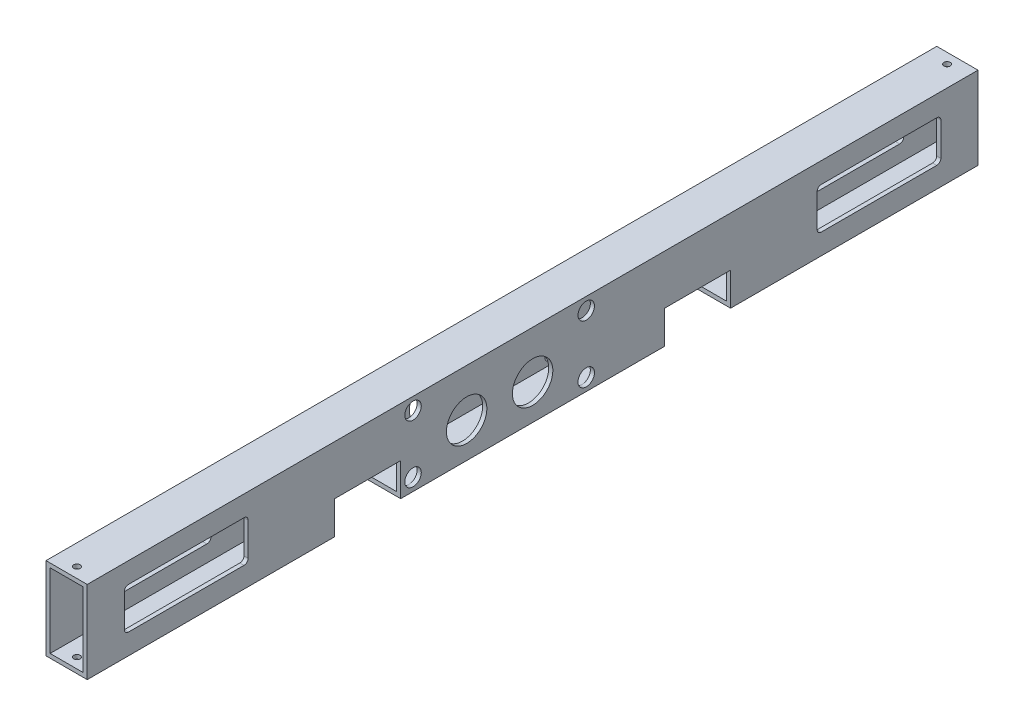
SolidWorks part; units mm, degrees
ref_plane "Front Plane" through (0, 0, 0) normal (0, 0, 1) x (1, 0, 0)
ref_plane "Top Plane" through (0, 0, 0) normal (0, 1, 0) x (1, 0, 0)
ref_plane "Right Plane" through (0, 0, 0) normal (1, 0, 0) x (0, 0, -1)
sketch "Sketch1" plane through (0, 0, 0) normal (0, 0, 1) x (1, 0, 0)
  line L1 (-12.1647, 2.5103) -> (19.5853, 2.5103)
  line L2 (-12.1647, 2.5103) -> (-12.1647, -60.9897)
  line L3 (-12.1647, -60.9897) -> (19.5853, -60.9897)
  line L4 (19.5853, 2.5103) -> (19.5853, -60.9897)
  line L5 (-8.9897, -0.6647) -> (16.4103, -0.6647)
  line L6 (-8.9897, -0.6647) -> (-8.9897, -57.8147)
  line L7 (-8.9897, -57.8147) -> (16.4103, -57.8147)
  line L8 (16.4103, -0.6647) -> (16.4103, -57.8147)
  dimension "D1" = 63.5
  dimension "D2" = 31.75
  dimension "D3" = 3.175
  dimension "D4" = 3.175
  dimension "D5" = 3.175
  dimension "D6" = 3.175
extrude "Boss-Extrude1" add sketch "Sketch1" along normal blind 685.8
sketch "Sketch3" plane through (-12.1647, 0, 0) normal (-1, 0, 0) x (0, 0, 1)
  line L0 (0, 2.5103) -> (0, -60.9897) construction
  line L1 (31.7754, -13.3647) -> (120.6754, -13.3647)
  line L2 (28.6004, -16.5397) -> (28.6004, -41.9397)
  line L3 (31.7754, -45.1147) -> (120.6754, -45.1147)
  line L4 (123.8504, -16.5397) -> (123.8504, -41.9397)
  line L5 (685.8, 2.5103) -> (0, 2.5103) construction
  line L6 (685.8, -60.9897) -> (0, -60.9897) construction
  line L7 (342.9, 2.5103) -> (342.9, -60.9897)
  line L8 (561.9496, -16.5397) -> (561.9496, -41.9397)
  line L9 (654.0246, -45.1147) -> (565.1246, -45.1147)
  line L10 (657.1996, -16.5397) -> (657.1996, -41.9397)
  line L11 (654.0246, -13.3647) -> (565.1246, -13.3647)
  line L12 (685.8, 2.5103) -> (685.8, -60.9897) construction
  line L13 (190.5, -60.9897) -> (241.3, -60.9897)
  line L14 (190.5, -60.9897) -> (190.5, -35.5897)
  line L15 (190.5, -35.5897) -> (241.3, -35.5897)
  line L16 (241.3, -60.9897) -> (241.3, -35.5897)
  line L17 (444.5, -60.9897) -> (495.3, -60.9897)
  line L18 (495.3, -60.9897) -> (495.3, -35.5897)
  line L19 (495.3, -35.5897) -> (444.5, -35.5897)
  line L20 (444.5, -60.9897) -> (444.5, -35.5897)
  arc A0 (28.6004, -41.9397) -> (31.7754, -45.1147) centre (31.7754, -41.9397) ccw
  arc A1 (120.6754, -45.1147) -> (123.8504, -41.9397) centre (120.6754, -41.9397) ccw
  arc A2 (120.6754, -13.3647) -> (123.8504, -16.5397) centre (120.6754, -16.5397) cw
  arc A3 (31.7754, -13.3647) -> (28.6004, -16.5397) centre (31.7754, -16.5397) ccw
  arc A4 (654.0246, -13.3647) -> (657.1996, -16.5397) centre (654.0246, -16.5397) cw
  arc A5 (565.1246, -13.3647) -> (561.9496, -16.5397) centre (565.1246, -16.5397) ccw
  arc A6 (565.1246, -45.1147) -> (561.9496, -41.9397) centre (565.1246, -41.9397) cw
  arc A7 (657.1996, -41.9397) -> (654.0246, -45.1147) centre (654.0246, -41.9397) cw
  line M7 (0, -60.9897) -> (685.8, -60.9897)
  dimension "D5" = 3.175
  dimension "D1" = 28.6004
  dimension "D2" = 15.875
  dimension "D3" = 15.875
  dimension "D4" = 95.25
  dimension "D6" = 25.4
  dimension "D7" = 50.8
  dimension "D8" = 190.5
  dimension "D9" = 50.8
  dimension "D10" = 25.4
  dimension "D11" = 190.5
extrude "Cut-Extrude1" cut sketch "Sketch3" against normal up to surface (31.75 mm away) contours L1 A3 L2 A0 L3 A1 L4 A2 | A7 L10 A4 L11 A5 L8 A6 L9 | L16 L15 L14 M7 | L20 L18 L19 M7 up to face at (19.5853, -29.2397, 342.9)
sketch "Sketch4" plane through (0, 2.5103, 0) normal (0, 1, 0) x (1, 0, 0)
  line L0 (19.5853, -685.8) -> (-12.1647, -685.8) construction
  line L1 (19.5853, 0) -> (-12.1647, 0) construction
  point P0 (3.7103, -677.8625)
  point P3 (3.7103, -685.8)
  point P4 (3.7103, -7.9375)
  dimension "D1" = 7.9375
  dimension "D2" = 7.9375
hole_wizard "#10 (0.1935) Diameter Hole1" positions "3DSketch1" profile "Sketch5" hole size "#10" standard "ANSI Inch" end condition through all
sketch3d "3DSketch1"
  point P0 (3.7103, 2.5103, 677.8625)
  point P3 (3.7103, 2.5103, 7.9375)
sketch "Sketch5" plane through (3.7103, 2.5103, 677.8625) normal (1, 0, 0) x (0, 0, 1)
  line L0 (0, 0) -> (0, 63.5)
  line L1 (0, 63.5) -> (2.4574, 63.5)
  line L2 (2.4574, 63.5) -> (2.4574, 0)
  line L5 (2.4574, 0) -> (0, 0)
  line L11 (0, -6.35) -> (0, 107.95) construction
  dimension "Thru Hole Dia." = 4.9149
  dimension "Thru Hole Depth" = 63.5
sketch "Sketch6" plane through (19.5853, 0, 0) normal (1, 0, 0) x (0, 0, -1)
  line L1 (-444.5, -60.9897) -> (-241.3, -60.9897) construction
  line L2 (-434.975, -7.0147) -> (-301.625, -7.0147) construction
  line L3 (-434.975, -7.0147) -> (-434.975, -51.4647) construction
  line L4 (-685.8, -60.9897) -> (-685.8, 2.5103) construction
  line L5 (-434.975, -51.4647) -> (-301.625, -51.4647) construction
  line L6 (-301.625, -7.0147) -> (-301.625, -51.4647) construction
  circle A0 centre (-342.9, -34.0022) radius 15.5575
  circle A1 centre (-393.7, -34.0022) radius 15.5575
  circle A2 centre (-434.975, -7.0147) radius 3.175
  circle A3 centre (-301.625, -7.0147) radius 3.175
  circle A4 centre (-434.975, -51.4647) radius 3.175
  circle A5 centre (-301.625, -51.4647) radius 3.175
  dimension "D1" = 31.115
  dimension "D4" = 50.8
  dimension "D6" = 17.4625
  dimension "D8" = 92.075
  dimension "D7" = 6.35
  dimension "D2" = 26.9875
  dimension "D3" = 342.9
  dimension "D5" = 26.9875
  dimension "D9" = 41.275
extrude "Cut-Extrude2" cut sketch "Sketch6" against normal up to surface (31.75 mm away) up to face at (-12.1647, -41.9397, 342.9)
sketch "Sketch7" plane through (19.5853, 0, 0) normal (1, 0, 0) x (0, 0, -1)
  circle A0 centre (-434.975, -7.0147) radius 6.35
  circle A1 centre (-434.975, -51.4647) radius 6.35
  circle A2 centre (-301.625, -51.4647) radius 6.35
  circle A3 centre (-301.625, -7.0147) radius 6.35
  dimension "D1" = 12.7
extrude "Cut-Extrude3" cut sketch "Sketch7" against normal up to next
